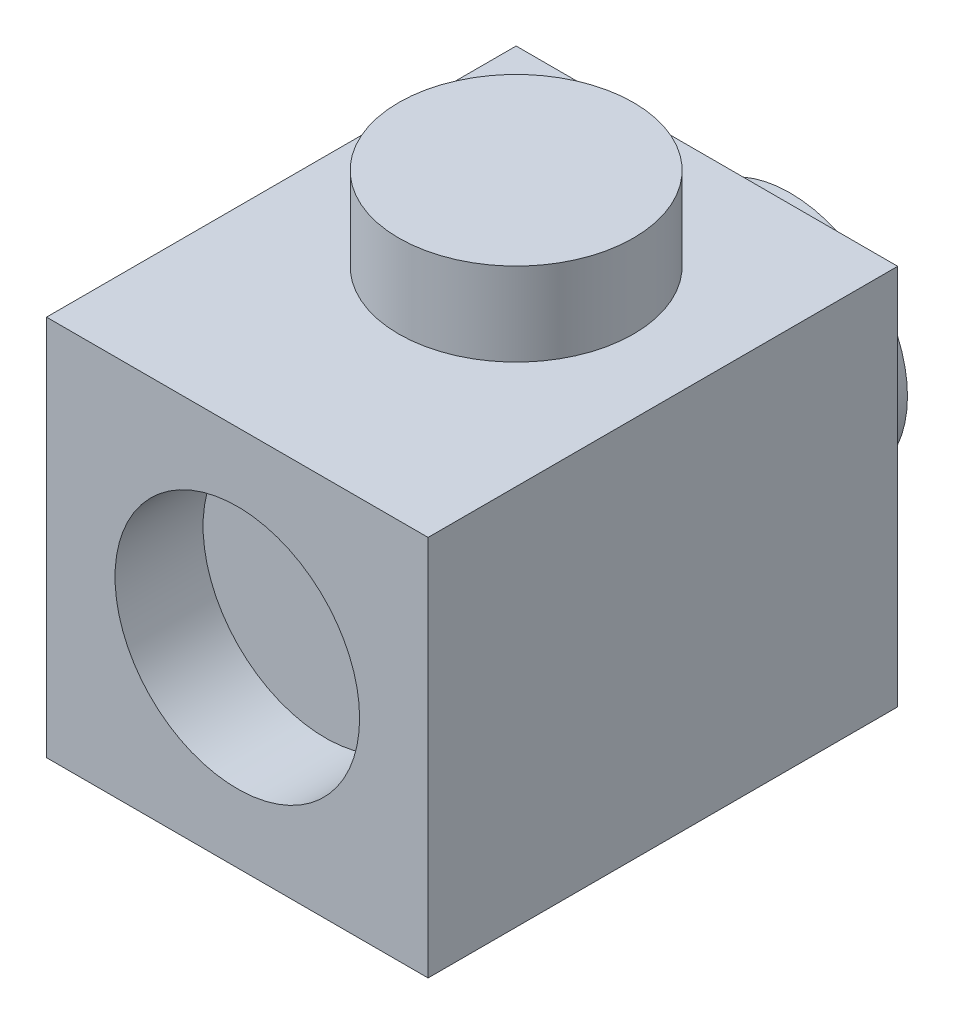
SolidWorks part; units mm, degrees
ref_plane "Спереди" through (0, 0, 0) normal (0, 0, 1) x (1, 0, 0)
ref_plane "Сверху" through (0, 0, 0) normal (0, 1, 0) x (1, 0, 0)
ref_plane "Справа" through (0, 0, 0) normal (1, 0, 0) x (0, 0, -1)
sketch "Эскиз1" plane through (0, 0, 0) normal (0, 0, 1) x (1, 0, 0)
  line L1 (-3.9, -3.9) -> (3.9, -3.9)
  line L2 (-3.9, -3.9) -> (-3.9, 3.9)
  line L3 (-3.9, 3.9) -> (3.9, 3.9)
  line L4 (3.9, -3.9) -> (3.9, 3.9)
  line L5 (-3.9, -3.9) -> (3.9, 3.9) construction
  line L6 (-3.9, 3.9) -> (3.9, -3.9) construction
  point P0 (0, 0)
  dimension "D1" = 7.8
  dimension "D2" = 7.8
extrude "Бобышка-Вытянуть1" add sketch "Эскиз1" along normal blind 9.6
sketch "Эскиз2" plane through (0, 0, 0) normal (0, 0, -1) x (-1, 0, 0)
  circle A0 centre (0, 0) radius 2.4
extrude "Бобышка-Вытянуть2" add sketch "Эскиз2" along normal blind 1.7
sketch "Эскиз3" plane through (0, 0, 9.6) normal (0, 0, 1) x (1, 0, 0)
  circle A0 centre (0, 0) radius 2.5
extrude "Вырез-Вытянуть1" cut sketch "Эскиз3" against normal blind 1.8
sketch "Эскиз5" plane through (0, 3.9, 0) normal (0, 1, 0) x (1, 0, 0)
  line L0 (3.9, 0) -> (-3.9, 0) construction
  circle A0 centre (0, -3.9) radius 2.4
  dimension "D1" = 3.9
extrude "Бобышка-Вытянуть3" add sketch "Эскиз5" along normal blind 1.7
